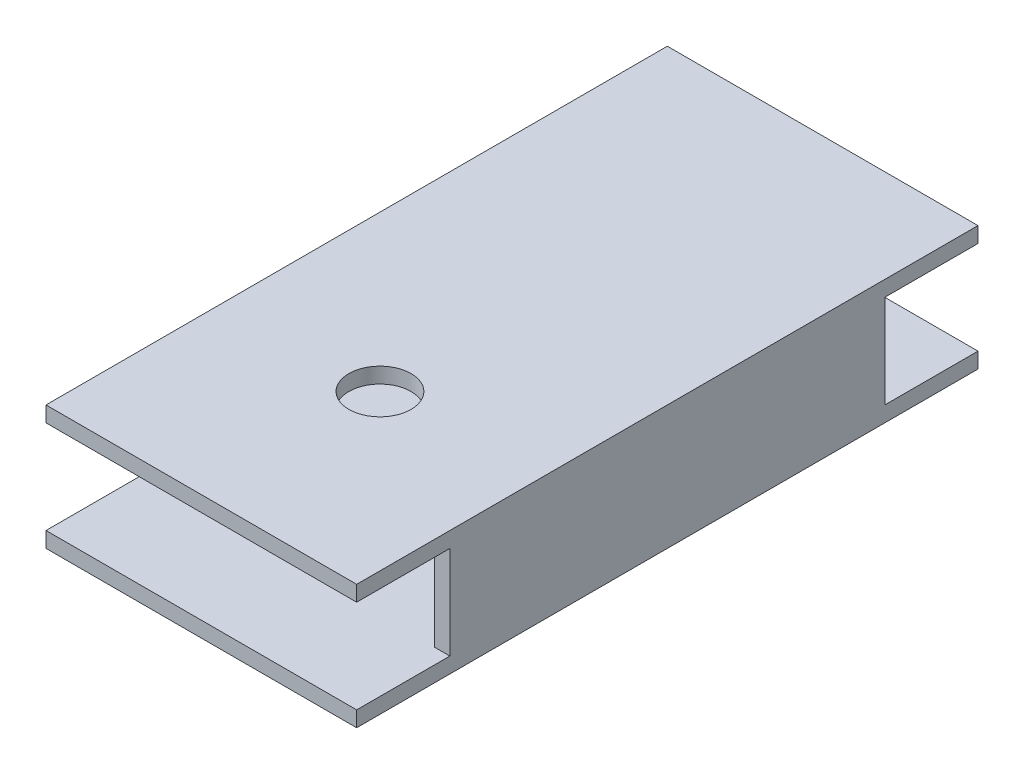
SolidWorks part; units mm, degrees
ref_plane "Front Plane" through (0, 0, 0) normal (0, 0, 1) x (1, 0, 0)
ref_plane "Top Plane" through (0, 0, 0) normal (0, 1, 0) x (1, 0, 0)
ref_plane "Right Plane" through (0, 0, 0) normal (1, 0, 0) x (0, 0, -1)
sketch "Sketch1" plane through (0, 0, 0) normal (0, 0, 1) x (1, 0, 0)
  line L1 (0, 0) -> (63.5, 0)
  line L2 (0, 0) -> (0, 25.4)
  line L3 (0, 25.4) -> (63.5, 25.4)
  line L4 (63.5, 0) -> (63.5, 25.4)
  dimension "D1" = 25.4
  dimension "D2" = 63.5
extrude "Extrude-Thin1" add sketch "Sketch1" along normal blind 127 thin thin type one direction reverse wall 3.175
sketch "Sketch2" plane through (63.5, 0, 0) normal (1, 0, 0) x (0, 0, -1)
  line L0 (0, 0) -> (0, 25.4) construction
  line L1 (0, 22.225) -> (-19.05, 22.225)
  line L2 (0, 22.225) -> (0, 3.175)
  line L3 (0, 3.175) -> (-19.05, 3.175)
  line L4 (-19.05, 22.225) -> (-19.05, 3.175)
  line L5 (-127, 25.4) -> (0, 25.4) construction
  line L6 (-127, 0) -> (0, 0) construction
  dimension "D1" = 3.175
  dimension "D2" = 3.175
  dimension "D3" = 19.05
extrude "Cut-Extrude1" cut sketch "Sketch2" against normal through all
sketch "Sketch3" plane through (63.5, 0, 0) normal (1, 0, 0) x (0, 0, -1)
  line L0 (-127, 0) -> (-127, 25.4) construction
  line L1 (-127, 22.225) -> (-107.95, 22.225)
  line L2 (-127, 22.225) -> (-127, 3.175)
  line L3 (-127, 3.175) -> (-107.95, 3.175)
  line L4 (-107.95, 22.225) -> (-107.95, 3.175)
  line L5 (-127, 25.4) -> (0, 25.4) construction
  line L6 (-127, 0) -> (0, 0) construction
  dimension "D1" = 3.175
  dimension "D2" = 3.175
  dimension "D3" = 19.05
extrude "Cut-Extrude2" cut sketch "Sketch3" against normal through all
sketch "Sketch4" plane through (0, 25.4, 0) normal (0, 1, 0) x (1, 0, 0)
  line L0 (63.5, -127) -> (0, -127) construction
  circle A0 centre (31.75, -90.4875) radius 6.35
  point P3 (31.75, 0)
  point P11 (36.7899, -63.5)
  dimension "D2" = 36.5125
  dimension "D1" = 12.7
extrude "Cut-Extrude3" cut sketch "Sketch4" against normal through all
